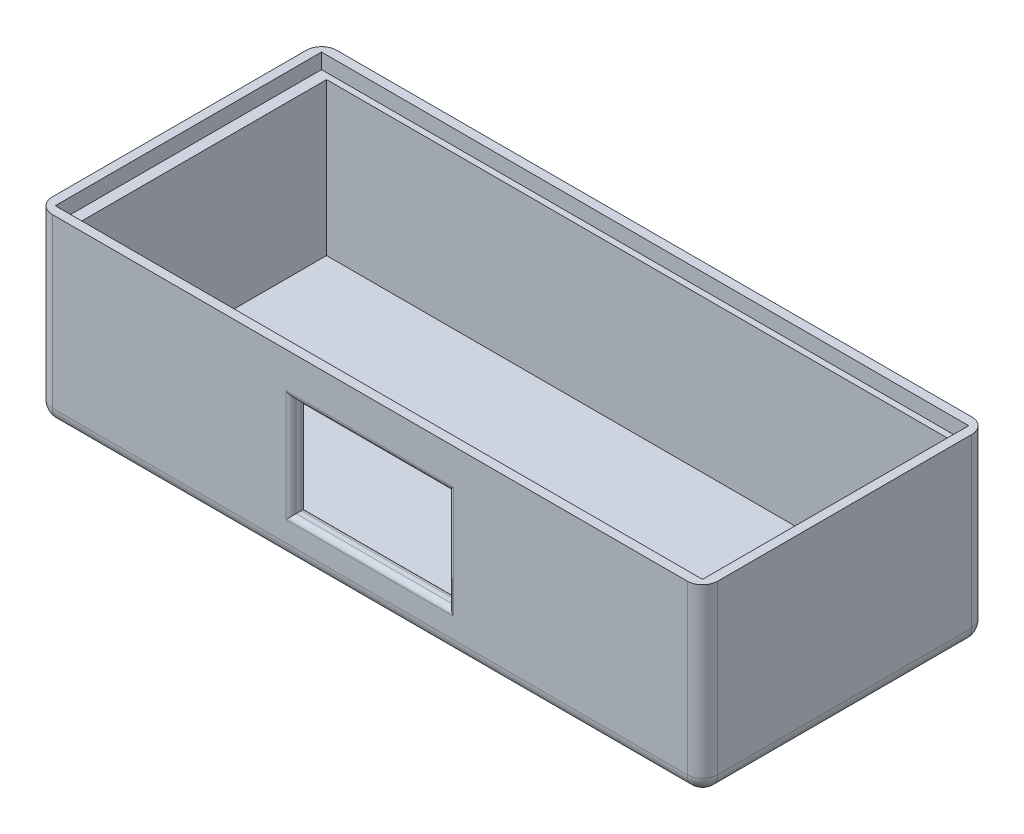
SolidWorks part; units mm, degrees
ref_plane "前视基准面" through (0, 0, 0) normal (0, 0, 1) x (1, 0, 0)
ref_plane "上视基准面" through (0, 0, 0) normal (0, 1, 0) x (1, 0, 0)
ref_plane "右视基准面" through (0, 0, 0) normal (1, 0, 0) x (0, 0, -1)
sketch "草图1" plane through (0, 0, 0) normal (0, 0, 1) x (1, 0, 0)
  line L0 (0, 0) -> (0, -30)
  line L1 (0, -30) -> (125, -30)
  line L2 (125, -30) -> (125, 0)
  line L3 (125, 0) -> (0, 0)
  line L4 (-3, 3) -> (-3, -33)
  line L6 (-3, 3) -> (128, 3)
  line L7 (128, 3) -> (128, -33)
  line L10 (-3, -33) -> (128, -33)
extrude "凸台-拉伸3" add sketch "草图1" along normal blind 50 contours L3 L0 L1 L2 | L6 L7 L10 L4
sketch "草图4" plane through (0, 0, 0) normal (0, 0, -1) x (-1, 0, 0)
  line L1 (-128, 3) -> (3, 3)
  line L2 (-128, 3) -> (-128, -33)
  line L3 (-128, -33) -> (3, -33)
  line L4 (3, 3) -> (3, -33)
extrude "凸台-拉伸4" add sketch "草图4" along normal blind 3
sketch "草图5" plane through (0, 3, 0) normal (0, 1, 0) x (1, 0, 0)
  circle A0 centre (17.5, -30) radius 7.5
  circle A1 centre (47.5, -30) radius 7.5
  circle A2 centre (77.5, -30) radius 7.5
  circle A3 centre (107.5, -30) radius 7.5
extrude "切除-拉伸1" cut sketch "草图5" against normal blind 3
sketch "草图6" plane through (0, -33, 0) normal (0, -1, 0) x (1, 0, 0)
  line L2 (10, 25) -> (10, 27.5)
  line L5 (115, 25) -> (115, 22.5)
  line L6 (115, 22.5) -> (10, 22.5)
  line L7 (10, 22.5) -> (10, 25)
  line L8 (10, 27.5) -> (115, 27.5)
  line L9 (115, 27.5) -> (115, 25)
extrude "切除-拉伸2" cut sketch "草图6" against normal blind 3
sketch "草图8" plane through (0, 0, 50) normal (0, 0, 1) x (1, 0, 0)
  line L1 (-3, 3) -> (128, 3)
  line L2 (-3, 3) -> (-3, -33)
  line L3 (-3, -33) -> (128, -33)
  line L4 (128, 3) -> (128, -33)
sketch "草图11" plane through (0, 0, 50) normal (0, 0, 1) x (1, 0, 0)
  line L0 (0, 0) -> (1, 0)
  line L1 (125, 0) -> (0, 0) construction
  line L2 (1, 0) -> (1, -30)
  line L3 (0, -30) -> (125, -30) construction
  line L4 (1, -30) -> (0, -30)
  line L5 (0, -30) -> (0, 0)
  line L6 (125, 0) -> (124, 0)
  line L7 (125, 0) -> (0, 0) construction
  line L8 (124, 0) -> (124, -30)
  line L9 (124, -30) -> (125, -30)
  line L10 (125, -30) -> (125, 0)
extrude "凸台-拉伸6" add sketch "草图11" against normal blind 50
extrude "凸台-拉伸7" add sketch "草图8" along normal blind 3
sketch "草图12" plane through (0, 3, 0) normal (0, 1, 0) x (1, 0, 0)
  line L12 (-1.2, 1.2) -> (126.2, 1.2)
  line L13 (-1.2, 1.2) -> (-1.2, -51.2)
  line L14 (-1.2, -51.2) -> (126.2, -51.2)
  line L15 (126.2, 1.2) -> (126.2, -51.2)
extrude "切除-拉伸4" cut sketch "草图12" against normal blind 3 contours L12 L15 L14 L13
sketch "草图13" plane through (0, 0, 53) normal (0, 0, 1) x (1, 0, 0)
  line L2 (47, -15) -> (47, -5)
  line L3 (47, -5) -> (78, -5)
  line L4 (78, -5) -> (78, -25)
  line L5 (78, -25) -> (47, -25)
  line L6 (47, -25) -> (47, -15)
extrude "切除-拉伸5" cut sketch "草图13" against normal blind 3
fillet "圆角5" radius 3 8 edges at (-3, -15, -3) (-3, -33, 25) (128, -33, 25) (62.5, -33, -3) (128, -15, -3) (128, -15, 53) (62.5, -33, 53) (-3, -15, 53)
fillet "圆角6" radius 1 8 edges at (62.5, -5, 50) (78, -15, 50) (62.5, -25, 50) (62.5, -25, 53) (78, -15, 53) (47, -15, 50) (62.5, -5, 53) (47, -15, 53)
